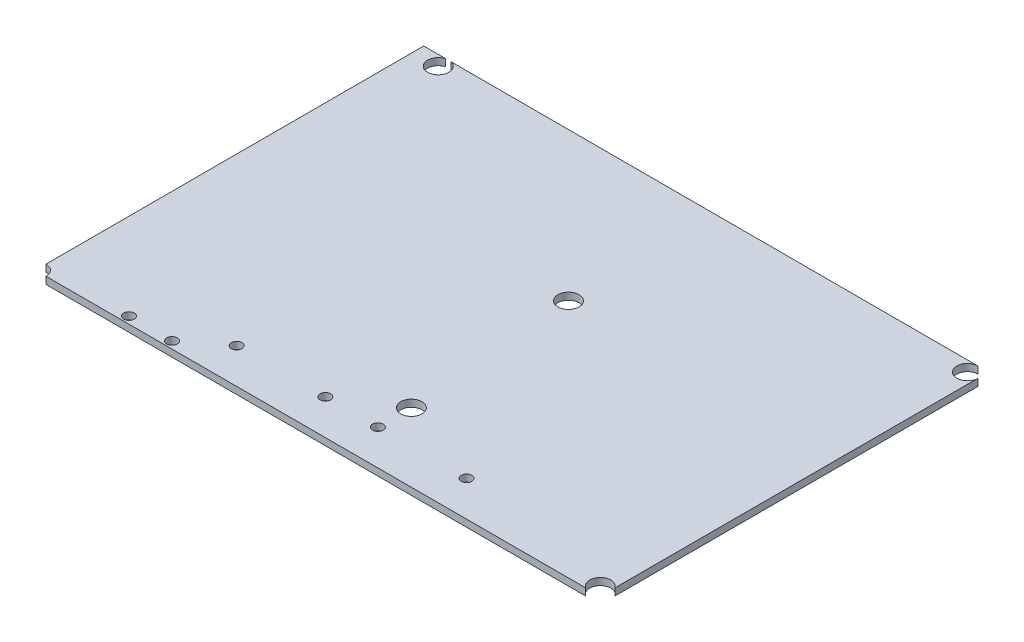
SolidWorks part; units mm, degrees
ref_plane "Ön Düzlem" through (0, 0, 0) normal (0, 0, 1) x (1, 0, 0)
ref_plane "Üst Düzlem" through (0, 0, 0) normal (0, 1, 0) x (1, 0, 0)
ref_plane "Sağ Düzlem" through (0, 0, 0) normal (1, 0, 0) x (0, 0, -1)
sketch "Çizim1" plane through (0, 0, 0) normal (0, 1, 0) x (1, 0, 0)
  line L0 (-80, 55) -> (80, -55) construction
  line L1 (-80, 55) -> (-73.7681, 55)
  line L2 (-80, 55) -> (-80, -52)
  line L3 (-77, -55) -> (75.8417, -55)
  line L4 (80, 52) -> (80, -50.8417)
  line L5 (-72.2319, 55) -> (77, 55)
  arc A0 (80, -50.8417) -> (75.8417, -55) centre (77.5, -52.5) ccw
  arc A1 (-77, -55) -> (-80, -52) centre (-80, -55) ccw
  arc A2 (-73.7681, 55) -> (-72.2319, 55) centre (-73, 52.1) ccw
  arc A3 (77, 55) -> (80, 52) centre (77, 52) ccw
  circle A4 centre (7, -35.5) radius 3
  circle A5 centre (3, 13) radius 3
  circle A6 centre (-33, -45) radius 1.5
  circle A7 centre (-7.88, -45) radius 1.5
  circle A8 centre (7, -45) radius 1.5
  circle A9 centre (32.12, -45) radius 1.5
  circle A10 centre (-55.5, -53) radius 1.5
  circle A11 centre (-43.3, -53) radius 1.5
  dimension "D3" = 2.5
  dimension "D4" = 6
  dimension "D6" = 6
  dimension "D7" = 7
  dimension "D8" = 6
  dimension "D9" = 3
  dimension "D11" = 6
  dimension "D14" = 42
  dimension "D16" = 25.12
  dimension "D19" = 47
  dimension "D1" = 110
  dimension "D2" = 2.9
  dimension "D5" = 2.5
  dimension "D10" = 3
  dimension "D12" = 87
  dimension "D13" = 19.5
  dimension "D15" = 83
  dimension "D17" = 25.12
  dimension "D18" = 87
  dimension "D20" = 12.2
  dimension "D21" = 24.5
  dimension "D22" = 2
  dimension "D23" = 10
  dimension "D24" = 10
extrude "Yükseklik-Ekstrüzyon1" add sketch "Çizim1" along normal blind 2
